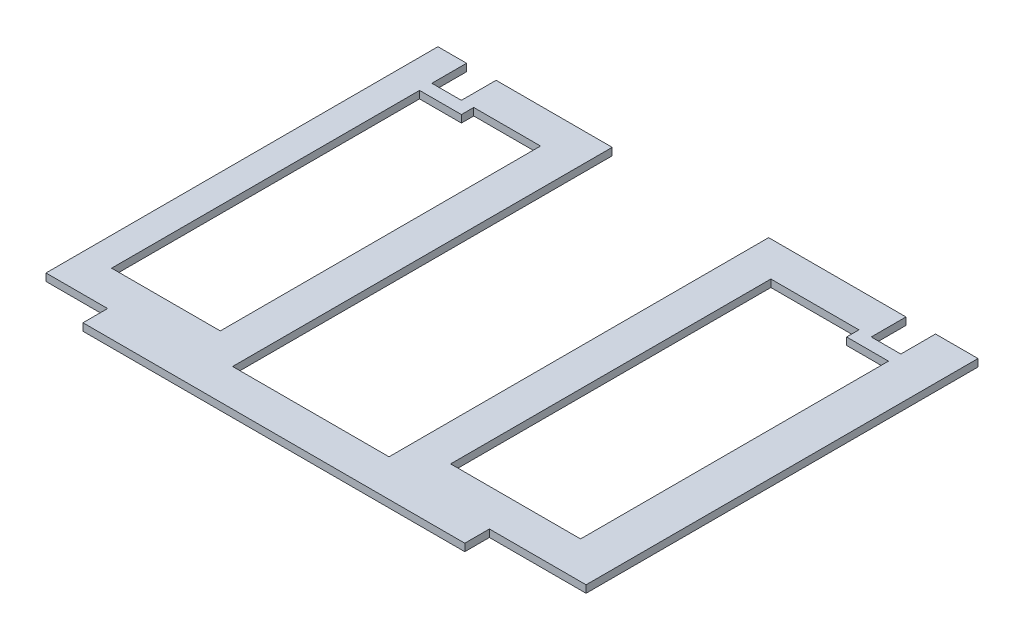
SolidWorks part; units mm, degrees
ref_plane "Front Plane" through (0, 0, 0) normal (0, 0, 1) x (1, 0, 0)
ref_plane "Top Plane" through (0, 0, 0) normal (0, 1, 0) x (1, 0, 0)
ref_plane "Right Plane" through (0, 0, 0) normal (1, 0, 0) x (0, 0, -1)
sketch "Sketch1" plane through (0, 0, 0) normal (0, 1, 0) x (1, 0, 0)
  line L0 (-112.62, 169.09) -> (-112.62, 0)
  line L1 (-112.62, 0) -> (112.62, 0)
  line L2 (112.62, 0) -> (112.62, 169.09)
  line L7 (112.62, 169.09) -> (-112.62, 169.09)
  dimension "D1" = 169.09
  dimension "D2" = 225.24
extrude "Boss-Extrude1" add sketch "Sketch1" along normal blind 3
sketch "Sketch2" plane through (0, 0, 0) normal (0, 1, 0) x (1, 0, 0)
  line L0 (112.62, 169.09) -> (-112.62, 169.09) construction
  line L5 (36.63, 25) -> (36.63, 155)
  line L10 (-100.99, 169.09) -> (-89, 169.09)
  line L11 (-100.99, 169.09) -> (-100.99, 25)
  line L12 (-100.99, 25) -> (-56.87, 25)
  line L13 (89.38, 169.09) -> (89.38, 25)
  line L14 (112.62, 0) -> (112.62, 169.09) construction
  line L15 (21.63, 169.09) -> (21.63, 15)
  line L16 (36.63, 25) -> (89.38, 25)
  line L17 (-112.62, 169.09) -> (-112.62, 0) construction
  line L18 (89.38, 169.09) -> (77.38, 169.09)
  line L19 (-56.87, 155) -> (-56.87, 25)
  line L20 (-41.87, 169.09) -> (-41.87, 15)
  line L21 (-41.87, 169.09) -> (21.63, 169.09)
  line L22 (-41.87, 15) -> (21.63, 15)
  line L23 (-112.62, 0) -> (112.62, 0) construction
  line L24 (112.62, 169.09) -> (-112.62, 169.09) construction
  line L26 (112.62, 0) -> (112.62, 169.09) construction
  line L27 (36.63, 155) -> (77.38, 155)
  line L28 (112.62, 0) -> (67.38, 0)
  line L29 (112.62, 0) -> (112.62, 10)
  line L30 (112.62, 10) -> (67.38, 10)
  line L31 (67.38, 0) -> (67.38, 10)
  line L32 (-112.62, 0) -> (-87.61, 0)
  line L33 (-112.62, 0) -> (-112.62, 10)
  line L34 (-112.62, 10) -> (-87.61, 10)
  line L35 (-87.61, 0) -> (-87.61, 10)
  line L36 (77.38, 155) -> (77.38, 169.09)
  line L37 (-56.87, 155) -> (-89, 155)
  line L38 (-89, 155) -> (-89, 169.09)
  point P3 (77.38, 162.045)
  dimension "D1" = 11.63
  dimension "D2" = 15
  dimension "D3" = 25
  dimension "D4" = 70.75
  dimension "D5" = 15
  dimension "D6" = 23.24
  dimension "D7" = 90.99
  dimension "D8" = 154.09
  dimension "D9" = 10
  dimension "D10" = 45.24
  dimension "D11" = 25.01
  dimension "D12" = 14.09
  dimension "D13" = 12
  dimension "D14" = 11.99
extrude "Cut-Extrude1" cut sketch "Sketch2" along normal through all
sketch "Sketch3" plane through (89.38, 0, 0) normal (-1, 0, 0) x (0, 0, 1)
  line L0 (-25, 0) -> (-169.09, 0) construction
  line L1 (-155, 0) -> (-150, 0)
  line L2 (-155, 0) -> (-155, 3)
  line L3 (-155, 3) -> (-150, 3)
  line L4 (-150, 0) -> (-150, 3)
  line L5 (-25, 3) -> (-169.09, 3) construction
  line L6 (-155, 3) -> (-155, 0) construction
  dimension "D1" = 5
extrude "Boss-Extrude2" add sketch "Sketch3" along normal blind 17
sketch "Sketch4" plane through (-100.99, 0, 0) normal (1, 0, 0) x (0, 0, -1)
  line L0 (169.09, 3) -> (25, 3) construction
  line L1 (155, 3) -> (150, 3)
  line L2 (155, 3) -> (155, 0)
  line L3 (155, 0) -> (150, 0)
  line L4 (150, 3) -> (150, 0)
  line L5 (169.09, 0) -> (25, 0) construction
  line L6 (155, 3) -> (155, 0) construction
  dimension "D1" = 5
extrude "Boss-Extrude3" add sketch "Sketch4" along normal blind 17
sketch "Sketch5" plane through (0, 3, 0) normal (0, 1, 0) x (1, 0, 0)
  line L0 (112.62, 169.09) -> (89.38, 169.09) construction
  line L1 (112.62, 10) -> (106.62, 10)
  line L2 (112.62, 10) -> (112.62, 169.09)
  line L3 (112.62, 169.09) -> (106.62, 169.09)
  line L4 (106.62, 10) -> (106.62, 169.09)
  dimension "D1" = 6
extrude "Cut-Extrude2" cut sketch "Sketch5" against normal through all
